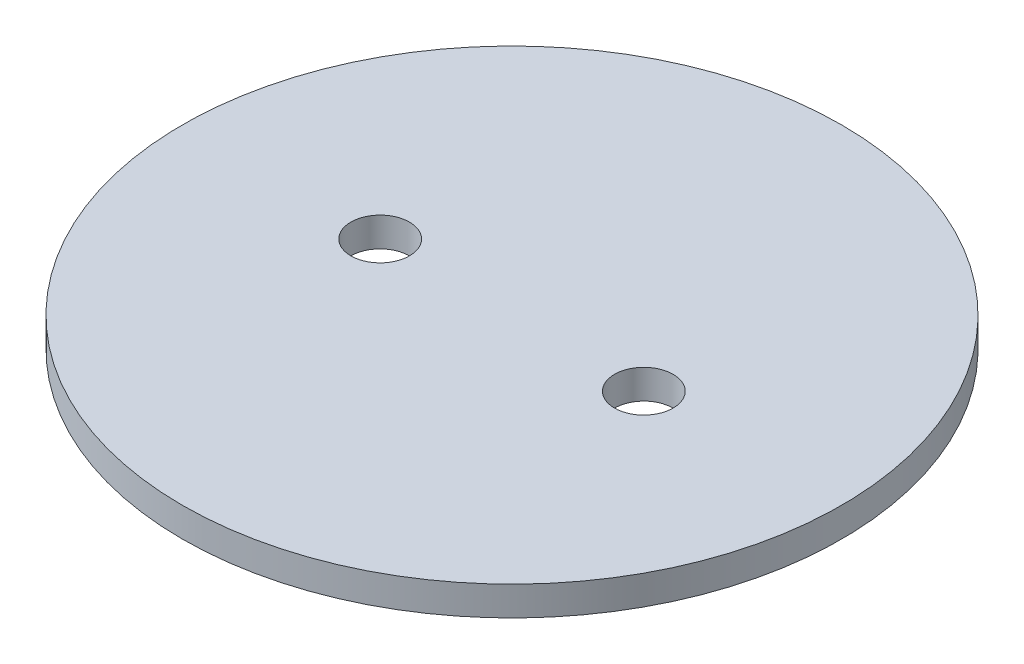
SolidWorks part; units mm, degrees
ref_plane "Front Plane" through (0, 0, 0) normal (0, 0, 1) x (1, 0, 0)
ref_plane "Top Plane" through (0, 0, 0) normal (0, 1, 0) x (1, 0, 0)
ref_plane "Right Plane" through (0, 0, 0) normal (1, 0, 0) x (0, 0, -1)
sketch "Sketch1" plane through (0, 0, 0) normal (0, 1, 0) x (1, 0, 0)
  circle A0 centre (0, 0) radius 4.5
extrude "Boss-Extrude1" add sketch "Sketch1" along normal blind 0.5
sketch "Sketch2" plane through (0, 0.5, 0) normal (0, 1, 0) x (1, 0, 0)
  circle A1 centre (-2.25, 0) radius 0.5
  circle A2 centre (2.25, 0) radius 0.5
extrude "Cut-Extrude1" cut sketch "Sketch2" against normal through all contours A1 | A2
sketch "Sketch3" plane through (0, 0.5, 0) normal (0, 1, 0) x (1, 0, 0)
  circle A0 centre (0, 0) radius 5.625
  circle A1 centre (0, 0) radius 4.5
extrude "Boss-Extrude2" add sketch "Sketch3" against normal blind 0.5 contours A0 | A1
